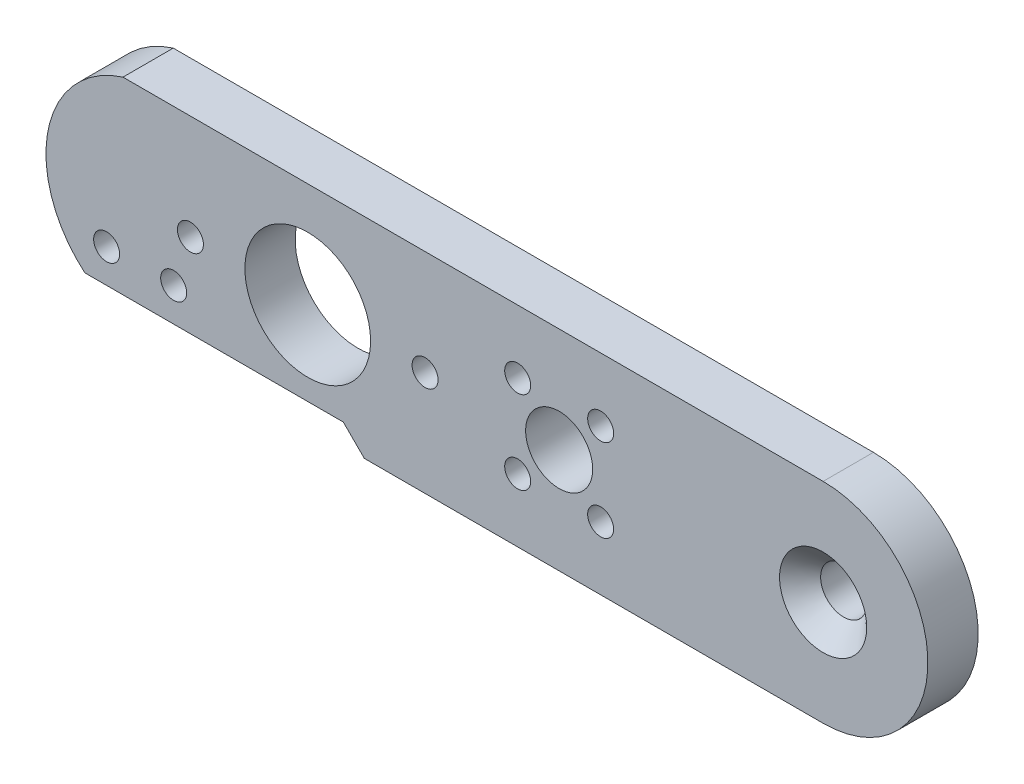
SolidWorks part; units mm, degrees
ref_plane "Front Plane" through (0, 0, 0) normal (0, 0, 1) x (1, 0, 0)
ref_plane "Top Plane" through (0, 0, 0) normal (0, 1, 0) x (1, 0, 0)
ref_plane "Right Plane" through (0, 0, 0) normal (1, 0, 0) x (0, 0, -1)
sketch "Sketch1" plane through (0, 0, 0) normal (0, 0, 1) x (1, 0, 0)
  line L0 (-46.4455, -10) -> (-15.599, -10)
  line L1 (-15.599, -10) -> (-13.099, -12.5)
  line L2 (-13.099, -12.5) -> (41.6532, -12.5)
  line L3 (-41.8959, 12.5) -> (41.6532, 12.5)
  line L4 (10.1535, 7) -> (10.1535, 0) construction
  line L5 (10.1535, 0) -> (15.1033, 4.9497) construction
  line L6 (10.1535, 0) -> (10.231, 0) construction
  line L7 (-37.9889, 0) -> (41.6532, 0) construction
  arc A1 (41.6532, -12.5) -> (41.6532, 12.5) centre (41.6532, 0) ccw
  arc A2 (-41.8959, 12.5) -> (-46.4455, -10) centre (-37.9889, 0) ccw
  circle A3 centre (10.1535, 0) radius 4
  circle A4 centre (10.1535, 0) radius 7 construction
  circle A5 centre (15.1033, 4.9497) radius 1.55
  circle A6 centre (5.2038, 4.9497) radius 1.55
  circle A7 centre (15.1033, -4.9497) radius 1.55
  circle A8 centre (5.2038, -4.9497) radius 1.55
  circle A9 centre (-33.8465, 0) radius 1.55
  circle A10 centre (-19.8465, 0) radius 7.5
  circle A11 centre (-5.8465, 0) radius 1.55
  dimension "D1" = 22.5
  dimension "D2" = 8
  dimension "D3" = 14
  dimension "D5" = 3.1
  dimension "D7" = 25
  dimension "D8" = 3.1
  dimension "D9" = 15
  dimension "D10" = 3.1
  dimension "D4" = 45
  dimension "D6" = 135
  dimension "D11" = 30
  dimension "D12" = 14
  dimension "D13" = 14
extrude "Boss-Extrude1" add sketch "Sketch1" along normal blind 6
hole_wizard "CSK for M5 Flat Head Machine Screw1" positions "Sketch5" profile "Sketch6" countersink size "M5" standard "ANSI Metric"
sketch "Sketch5" plane through (0, 0, 6) normal (0, 0, 1) x (1, 0, 0)
  point P0 (41.6532, 0)
sketch "Sketch6" plane through (41.6532, 0, 6) normal (1, 0, 0) x (0, -1, 0)
  line L0 (0, 0) -> (0, 15)
  line L1 (0, 15) -> (2.75, 13.3476)
  line L2 (2.75, 13.3476) -> (2.75, 2.45)
  line L3 (2.75, 2.45) -> (5.2, 0)
  line L5 (5.2, 0) -> (0, 0)
  line L6 (-2.75, 2.45) -> (-5.2, 0) construction
  line L10 (0, 15) -> (-2.75, 13.3476) construction
  line L11 (0, -6.35) -> (0, 107.95) construction
  dimension "Hole Dia." = 5.5
  dimension "Hole Depth" = 15
  dimension "Near C'Sink Dia." = 10.4
  dimension "Near C'Sink Angle" = 90
  dimension "Drill Angle" = 118
sketch "Sketch7" plane through (0, 0, 6) normal (0, 0, 1) x (1, 0, 0)
  line L0 (-45.7719, -6) -> (-29.2933, -6) construction
  line L1 (41.6532, 12.5) -> (-41.8959, 12.5) construction
  circle A0 centre (-43.8465, -6) radius 1.55
  circle A1 centre (-35.8465, -6) radius 1.55
  circle A2 centre (-19.8465, 0) radius 7.5 construction
  dimension "D2" = 3.1
  dimension "D5" = 3.1
  dimension "D1" = 18.5
  dimension "D3" = 8
  dimension "D4" = 16
extrude "Cut-Extrude1" cut sketch "Sketch7" against normal blind 3
sketch "Sketch8" plane through (0, 0, 3) normal (0, 0, 1) x (1, 0, 0)
  circle A0 centre (-35.8465, -6) radius 3
  circle A1 centre (-43.8465, -6) radius 3
  dimension "D1" = 6
extrude "Cut-Extrude2" cut sketch "Sketch8" against normal through all
